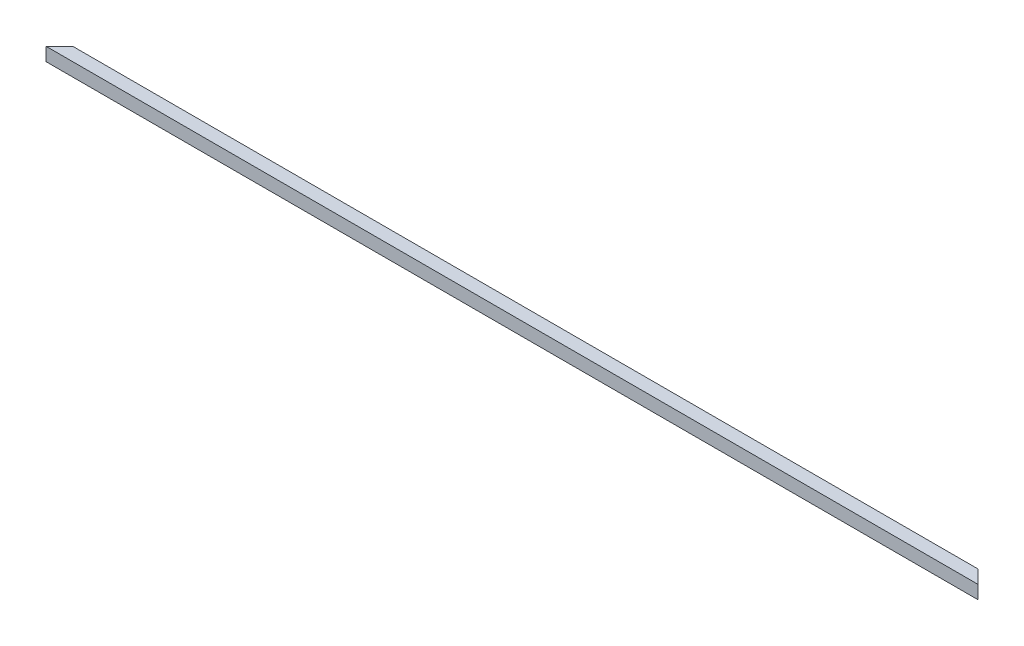
SolidWorks part; units mm, degrees
ref_plane "Front Plane" through (0, 0, 0) normal (0, 0, 1) x (1, 0, 0)
ref_plane "Top Plane" through (0, 0, 0) normal (0, 1, 0) x (1, 0, 0)
ref_plane "Right Plane" through (0, 0, 0) normal (1, 0, 0) x (0, 0, -1)
sketch "Sketch1" plane through (0, 0, 0) normal (0, 1, 0) x (1, 0, 0)
  line L0 (0, 0) -> (1397, 0)
  line L1 (1397, 0) -> (1377, 20)
  line L2 (1377, 20) -> (20, 20)
  line L3 (20, 20) -> (0, 0)
  dimension "D1" = 1397
  dimension "D2" = 45
  dimension "D3" = 45
  dimension "D4" = 20
extrude "Boss-Extrude1" add sketch "Sketch1" along normal blind 20
